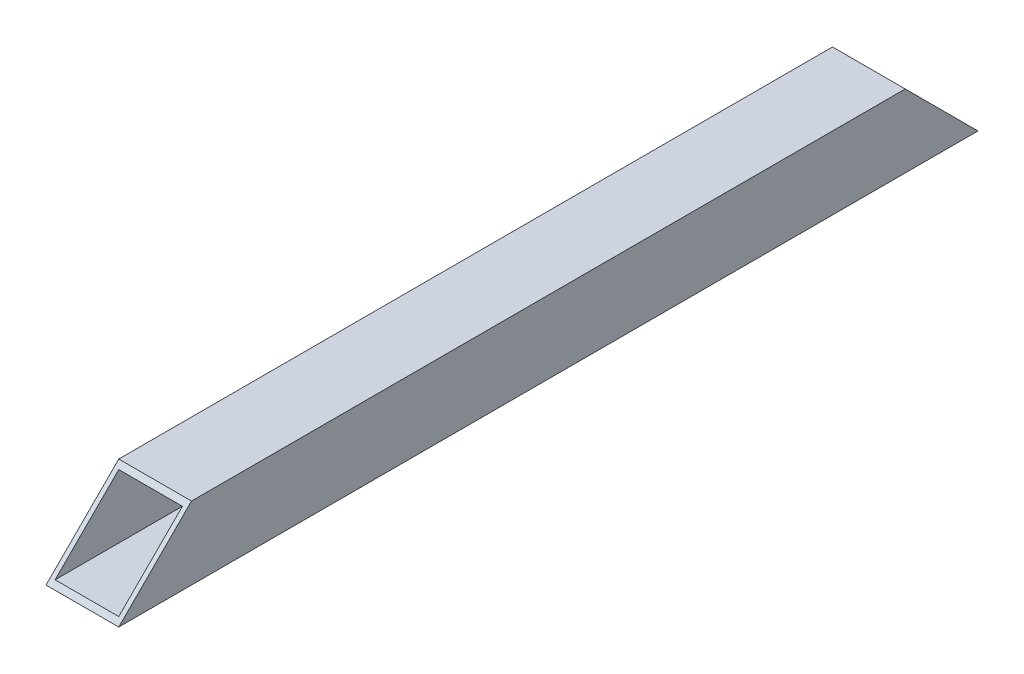
SolidWorks part; units mm, degrees
material "6061-T6 (SS)"
ref_plane "Front Plane" through (0, 0, 0) normal (0, 0, 1) x (1, 0, 0)
ref_plane "Top Plane" through (0, 0, 0) normal (0, 1, 0) x (1, 0, 0)
ref_plane "Right Plane" through (0, 0, 0) normal (1, 0, 0) x (0, 0, -1)
sketch "Sketch1" plane through (0, 0, 0) normal (0, 0, 1) x (1, 0, 0)
  line L1 (12.7, -12.7) -> (-12.7, -12.7)
  line L2 (12.7, -12.7) -> (12.7, 12.7)
  line L3 (12.7, 12.7) -> (-12.7, 12.7)
  line L4 (-12.7, -12.7) -> (-12.7, 12.7)
  line L5 (12.7, -12.7) -> (-12.7, 12.7) construction
  line L6 (12.7, 12.7) -> (-12.7, -12.7) construction
  line L7 (11.1125, -11.1125) -> (-11.1125, -11.1125)
  line L8 (11.1125, -11.1125) -> (11.1125, 11.1125)
  line L9 (11.1125, 11.1125) -> (-11.1125, 11.1125)
  line L10 (-11.1125, -11.1125) -> (-11.1125, 11.1125)
  line L11 (11.1125, -11.1125) -> (-11.1125, 11.1125) construction
  line L12 (11.1125, 11.1125) -> (-11.1125, -11.1125) construction
  point P0 (0, 0)
  point P6 (0, 0)
  point P11 (-12.7, 0)
  dimension "D1" = 25.4
  dimension "D2" = 25.4
  dimension "D3" = 1.5875
  dimension "D4" = 1.5875
extrude "Boss-Extrude1" add sketch "Sketch1" along normal mid plane 300
sketch "Sketch2" plane through (12.7, 0, 0) normal (1, 0, 0) x (0, 0, -1)
  line L0 (-150, -12.7) -> (-150, 12.7)
  line L1 (-150, 12.7) -> (-124.6, 12.7)
  line L2 (-150, 12.7) -> (150, 12.7) construction
  line L3 (-124.6, 12.7) -> (-150, -12.7)
  line L4 (150, -12.7) -> (150, 12.7)
  line L5 (150, 12.7) -> (124.6, 12.7)
  line L6 (124.6, 12.7) -> (150, -12.7)
  dimension "D1" = 45
  dimension "D2" = 45
extrude "Cut-Extrude1" cut sketch "Sketch2" against normal through all
